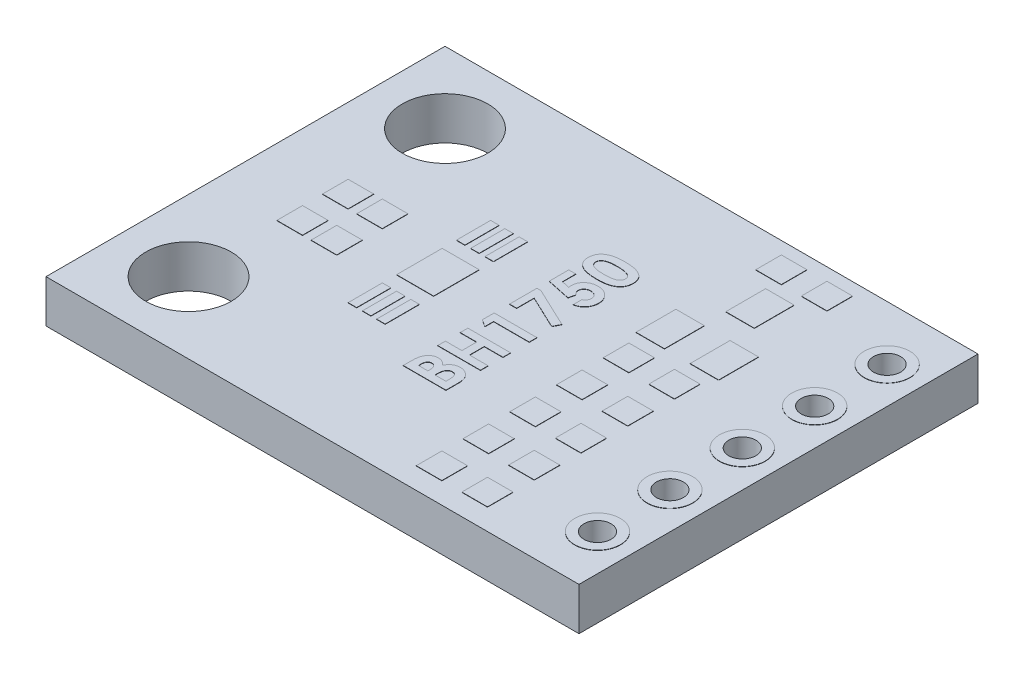
SolidWorks part; units mm, degrees
ref_plane "Спереди" through (0, 0, 0) normal (0, 0, 1) x (1, 0, 0)
ref_plane "Сверху" through (0, 0, 0) normal (0, 1, 0) x (1, 0, 0)
ref_plane "Справа" through (0, 0, 0) normal (1, 0, 0) x (0, 0, -1)
sketch "Эскиз1" plane through (0, 0, 0) normal (0, 1, 0) x (1, 0, 0)
  line L1 (0, 0) -> (18.7, 0)
  line L2 (0, 0) -> (0, 14)
  line L3 (0, 14) -> (18.7, 14)
  line L4 (18.7, 0) -> (18.7, 14)
  circle A0 centre (2.5, 11.5) radius 1.5
  circle A1 centre (2.5, 2.5) radius 1.5
  circle A4 centre (17.43, 1.92) radius 0.475
  circle A6 centre (17.43, 4.46) radius 0.475
  circle A8 centre (17.43, 7) radius 0.475
  circle A9 centre (17.43, 9.54) radius 0.475
  circle A10 centre (17.43, 12.08) radius 0.475
  point P8 (17.43, 12.08)
  dimension "D1" = 18.7
  dimension "D2" = 14
extrude "Бобышка-Вытянуть1" add sketch "Эскиз1" along normal blind 1.5
sketch "Эскиз2" plane through (0, 1.5, 0) normal (0, 1, 0) x (1, 0, 0)
  line L5 (13.15, 6.56) -> (12.25, 6.56)
  line L6 (14.75, 12.65) -> (13.85, 13.55) construction
  line L7 (14.75, 13.55) -> (13.85, 12.65) construction
  line L8 (12.25, 13.55) -> (13.15, 13.55)
  line L9 (12.25, 13.55) -> (12.25, 12.65)
  line L10 (12.25, 12.65) -> (13.15, 12.65)
  line L11 (13.15, 13.55) -> (13.15, 12.65)
  line L12 (12.25, 13.55) -> (13.15, 12.65) construction
  line L13 (12.25, 12.65) -> (13.15, 13.55) construction
  line L14 (13.85, 13.55) -> (13.85, 12.65)
  line L15 (14.75, 12.65) -> (13.85, 12.65)
  line L16 (14.75, 13.55) -> (14.75, 12.65)
  line L17 (14.75, 13.55) -> (13.85, 13.55)
  line L18 (13.15, 6.56) -> (13.15, 5.66)
  line L19 (13.15, 5.66) -> (12.25, 5.66)
  line L20 (14, 12.25) -> (13, 12.25)
  line L21 (14, 12.25) -> (14, 10.85)
  line L22 (14, 10.85) -> (13, 10.85)
  line L23 (13, 12.25) -> (13, 10.85)
  line L24 (14, 12.25) -> (13, 10.85) construction
  line L25 (14, 10.85) -> (13, 12.25) construction
  line L26 (12.25, 6.56) -> (12.25, 5.66)
  line L27 (13.95, 8.65) -> (14.95, 10.05) construction
  line L28 (13.05, 10.05) -> (12.05, 10.05)
  line L29 (13.05, 10.05) -> (13.05, 8.65)
  line L30 (13.05, 8.65) -> (12.05, 8.65)
  line L31 (12.05, 10.05) -> (12.05, 8.65)
  line L32 (13.05, 10.05) -> (12.05, 8.65) construction
  line L33 (13.05, 8.65) -> (12.05, 10.05) construction
  line L34 (13.95, 10.05) -> (14.95, 8.65) construction
  line L35 (14.95, 10.05) -> (14.95, 8.65)
  line L36 (13.95, 8.65) -> (14.95, 8.65)
  line L37 (13.95, 10.05) -> (13.95, 8.65)
  line L38 (13.95, 10.05) -> (14.95, 10.05)
  line L40 (14.75, 6.56) -> (14.75, 5.66)
  line L41 (13.85, 5.66) -> (14.75, 5.66)
  line L42 (13.85, 7.3) -> (14.75, 8.2) construction
  line L43 (13.15, 8.2) -> (12.25, 8.2)
  line L44 (13.15, 8.2) -> (13.15, 7.3)
  line L45 (13.15, 7.3) -> (12.25, 7.3)
  line L46 (12.25, 8.2) -> (12.25, 7.3)
  line L47 (13.15, 8.2) -> (12.25, 7.3) construction
  line L48 (13.15, 7.3) -> (12.25, 8.2) construction
  line L49 (13.85, 8.2) -> (14.75, 7.3) construction
  line L50 (14.75, 8.2) -> (14.75, 7.3)
  line L51 (13.85, 7.3) -> (14.75, 7.3)
  line L52 (13.85, 8.2) -> (13.85, 7.3)
  line L53 (13.85, 8.2) -> (14.75, 8.2)
  line L54 (13.85, 6.56) -> (13.85, 5.66)
  line L55 (13.85, 6.56) -> (14.75, 6.56)
  line L56 (13.85, 5.66) -> (14.75, 6.56) construction
  line L57 (13.15, 6.56) -> (12.25, 5.66) construction
  line L58 (13.15, 5.66) -> (12.25, 6.56) construction
  line L59 (13.85, 6.56) -> (14.75, 5.66) construction
  line L60 (13.15, 4.92) -> (12.25, 4.92)
  line L61 (13.15, 4.92) -> (13.15, 4.02)
  line L62 (13.15, 4.02) -> (12.25, 4.02)
  line L63 (12.25, 4.92) -> (12.25, 4.02)
  line L64 (14.75, 4.92) -> (14.75, 4.02)
  line L65 (13.85, 4.02) -> (14.75, 4.02)
  line L66 (13.85, 4.92) -> (13.85, 4.02)
  line L67 (13.85, 4.92) -> (14.75, 4.92)
  line L68 (13.85, 4.02) -> (14.75, 4.92) construction
  line L69 (13.15, 4.92) -> (12.25, 4.02) construction
  line L70 (13.15, 4.02) -> (12.25, 4.92) construction
  line L71 (13.85, 4.92) -> (14.75, 4.02) construction
  line L72 (13.15, 3.28) -> (12.25, 3.28)
  line L73 (13.15, 3.28) -> (13.15, 2.38)
  line L74 (13.15, 2.38) -> (12.25, 2.38)
  line L75 (12.25, 3.28) -> (12.25, 2.38)
  line L76 (14.75, 3.28) -> (14.75, 2.38)
  line L77 (13.85, 2.38) -> (14.75, 2.38)
  line L78 (13.85, 3.28) -> (13.85, 2.38)
  line L79 (13.85, 3.28) -> (14.75, 3.28)
  line L80 (13.85, 2.38) -> (14.75, 3.28) construction
  line L81 (13.15, 3.28) -> (12.25, 2.38) construction
  line L82 (13.15, 2.38) -> (12.25, 3.28) construction
  line L83 (13.85, 3.28) -> (14.75, 2.38) construction
  line L84 (13.15, 1.64) -> (12.25, 1.64)
  line L85 (13.15, 1.64) -> (13.15, 0.74)
  line L86 (13.15, 0.74) -> (12.25, 0.74)
  line L87 (12.25, 1.64) -> (12.25, 0.74)
  line L88 (14.75, 1.64) -> (14.75, 0.74)
  line L89 (13.85, 0.74) -> (14.75, 0.74)
  line L90 (13.85, 1.64) -> (13.85, 0.74)
  line L91 (13.85, 1.64) -> (14.75, 1.64)
  line L92 (13.85, 0.74) -> (14.75, 1.64) construction
  line L93 (13.15, 1.64) -> (12.25, 0.74) construction
  line L94 (13.15, 0.74) -> (12.25, 1.64) construction
  line L95 (13.85, 1.64) -> (14.75, 0.74) construction
  line L98 (4.45, 6.65) -> (3.55, 6.65)
  line L99 (3.25, 8.25) -> (2.35, 7.35) construction
  line L100 (3.25, 6.65) -> (2.35, 6.65)
  line L101 (3.25, 6.65) -> (3.25, 5.75)
  line L102 (3.25, 5.75) -> (2.35, 5.75)
  line L103 (2.35, 6.65) -> (2.35, 5.75)
  line L104 (3.25, 6.65) -> (2.35, 5.75) construction
  line L105 (3.25, 5.75) -> (2.35, 6.65) construction
  line L106 (3.25, 7.35) -> (2.35, 8.25) construction
  line L107 (2.35, 7.35) -> (2.35, 8.25)
  line L108 (3.25, 8.25) -> (2.35, 8.25)
  line L109 (3.25, 7.35) -> (3.25, 8.25)
  line L110 (3.25, 7.35) -> (2.35, 7.35)
  line L111 (4.45, 6.65) -> (4.45, 5.75)
  line L112 (4.45, 5.75) -> (3.55, 5.75)
  line L113 (3.55, 6.65) -> (3.55, 5.75)
  line L114 (3.55, 7.35) -> (3.55, 8.25)
  line L115 (4.45, 8.25) -> (3.55, 8.25)
  line L116 (4.45, 7.35) -> (4.45, 8.25)
  line L117 (4.45, 7.35) -> (3.55, 7.35)
  line L118 (4.45, 8.25) -> (3.55, 7.35) construction
  line L119 (4.45, 6.65) -> (3.55, 5.75) construction
  line L120 (4.45, 5.75) -> (3.55, 6.65) construction
  line L121 (4.45, 7.35) -> (3.55, 8.25) construction
  line L125 (6.1, 6.2) -> (7.4, 6.2)
  line L126 (6.1, 6.2) -> (6.1, 7.8)
  line L127 (6.1, 7.8) -> (7.4, 7.8)
  line L128 (7.4, 6.2) -> (7.4, 7.8)
  line L129 (6.1, 6.2) -> (7.4, 7.8) construction
  line L130 (6.1, 7.8) -> (7.4, 6.2) construction
  line L131 (7.1, 8.3) -> (7.4, 8.3)
  line L136 (6.6, 8.3) -> (6.9, 9.5) construction
  line L137 (6.6, 9.5) -> (6.9, 8.3) construction
  line L138 (7.1, 8.3) -> (7.1, 9.5)
  line L139 (7.1, 9.5) -> (7.4, 9.5)
  line L140 (7.4, 8.3) -> (7.4, 9.5)
  line L141 (7.1, 8.3) -> (7.4, 9.5) construction
  line L142 (7.1, 9.5) -> (7.4, 8.3) construction
  line L143 (6.6, 8.3) -> (6.9, 8.3)
  line L144 (6.6, 8.3) -> (6.6, 9.5)
  line L145 (6.6, 9.5) -> (6.9, 9.5)
  line L146 (6.9, 8.3) -> (6.9, 9.5)
  line L147 (6.6, 8.3) -> (6.9, 9.5) construction
  line L148 (6.6, 9.5) -> (6.9, 8.3) construction
  line L149 (6.1, 8.3) -> (6.4, 8.3)
  line L150 (6.1, 8.3) -> (6.1, 9.5)
  line L151 (6.1, 9.5) -> (6.4, 9.5)
  line L152 (6.4, 8.3) -> (6.4, 9.5)
  line L153 (6.1, 8.3) -> (6.4, 9.5) construction
  line L154 (6.1, 9.5) -> (6.4, 8.3) construction
  line L155 (6.1, 4.5) -> (6.4, 5.7) construction
  line L156 (6.1, 5.7) -> (6.4, 4.5) construction
  line L157 (6.6, 4.5) -> (6.9, 5.7) construction
  line L158 (6.6, 5.7) -> (6.9, 4.5) construction
  line L159 (7.1, 4.5) -> (7.4, 5.7) construction
  line L160 (7.1, 5.7) -> (7.4, 4.5) construction
  line L161 (6.6, 4.5) -> (6.9, 5.7) construction
  line L162 (6.6, 5.7) -> (6.9, 4.5) construction
  line L163 (6.4, 5.7) -> (6.4, 4.5)
  line L164 (6.1, 4.5) -> (6.4, 4.5)
  line L165 (6.1, 5.7) -> (6.1, 4.5)
  line L166 (6.1, 5.7) -> (6.4, 5.7)
  line L171 (7.4, 5.7) -> (7.4, 4.5)
  line L172 (7.1, 4.5) -> (7.4, 4.5)
  line L173 (7.1, 5.7) -> (7.1, 4.5)
  line L174 (6.9, 5.7) -> (6.9, 4.5)
  line L175 (6.6, 4.5) -> (6.9, 4.5)
  line L176 (6.6, 5.7) -> (6.6, 4.5)
  line L177 (6.6, 5.7) -> (6.9, 5.7)
  line L178 (7.1, 5.7) -> (7.4, 5.7)
  circle A0 centre (17.43, 12.08) radius 0.475
  circle A1 centre (17.43, 12.08) radius 0.8
  circle A2 centre (17.43, 9.54) radius 0.475
  circle A3 centre (17.43, 9.54) radius 0.8
  circle A4 centre (17.43, 7) radius 0.475
  circle A5 centre (17.43, 7) radius 0.8
  circle A6 centre (17.43, 4.46) radius 0.475
  circle A7 centre (17.43, 4.46) radius 0.8
  circle A8 centre (17.43, 1.92) radius 0.475
  circle A9 centre (17.43, 1.92) radius 0.8
  dimension "D20" = 5
  dimension "D1" = 0.9
  dimension "D2" = 0.9
  dimension "D3" = 1.4
  dimension "D4" = 1
  dimension "D5" = 1
  dimension "D6" = 1.4
  dimension "D7" = 0.9
  dimension "D8" = 0.9
  dimension "D9" = 0.9
  dimension "D11" = 0.9
  dimension "D12" = 0.9
  dimension "D14" = 1.6
  dimension "D15" = 1.3
  dimension "D16" = 1.2
  dimension "D17" = 0.3
  dimension "D10" = 5
  dimension "D13" = 2
  dimension "D18" = 2
  dimension "D19" = 2
extrude "Бобышка-Вытянуть2" add sketch "Эскиз2" along normal blind 0.01
sketch "Эскиз3" plane through (0, 1.5, 0) normal (0, 1, 0) x (1, 0, 0)
  line L6 (0, 0) -> (18.7, 0) construction
  line L7 (10.475, 0) -> (10.475, 14) construction
  line L8 (18.7, 14) -> (0, 14) construction
  text T1 "<b>BH1750</b>" font "Century Gothic" height 1.5
extrude "Бобышка-Вытянуть4" add sketch "Эскиз3" along normal blind 0.01
sketch "Эскиз5" plane through (0, 0, 0) normal (0, -1, 0) x (1, 0, 0)
  line L0 (15.455, -3.96) -> (9.455, -3.96) construction
  line L2 (15.455, -1.42) -> (9.455, -1.42) construction
  line L3 (15.455, -6.5) -> (9.455, -6.5) construction
  line L4 (15.455, -9.04) -> (9.455, -9.04) construction
  line L5 (15.455, -11.58) -> (9.455, -11.58) construction
  line L6 (7.2275, 0) -> (7.2275, -14) construction
  text T0 "<b>ADDR</b>" font "Century Gothic" height 1
  text T1 "<b>SDA</b>" font "Century Gothic" height 1
  text T2 "<b>SCL</b>" font "Century Gothic" height 1
  text T3 "<b>GND</b>" font "Century Gothic" height 1
  text T4 "<b>VCC</b>" font "Century Gothic" height 1
  text T5 "<b>GY-302</b>" font "Century Gothic" height 1
extrude "Бобышка-Вытянуть6" add sketch "Эскиз5" along normal blind 0.01
sketch "Эскиз6" plane through (0, 0, 0) normal (0, -1, 0) x (1, 0, 0)
  circle A0 centre (17.43, -1.92) radius 0.4757
  circle A1 centre (17.43, -1.92) radius 0.8
  circle A2 centre (17.43, -4.46) radius 0.4757
  circle A3 centre (17.43, -4.46) radius 0.8
  circle A4 centre (17.43, -7) radius 0.4757
  circle A5 centre (17.43, -7) radius 0.8
  circle A6 centre (17.43, -9.54) radius 0.4757
  circle A7 centre (17.43, -9.54) radius 0.8
  circle A8 centre (17.43, -12.08) radius 0.4757
  circle A9 centre (17.43, -12.08) radius 0.8
  dimension "D1" = 5
extrude "Бобышка-Вытянуть7" add sketch "Эскиз6" along normal blind 0.01
